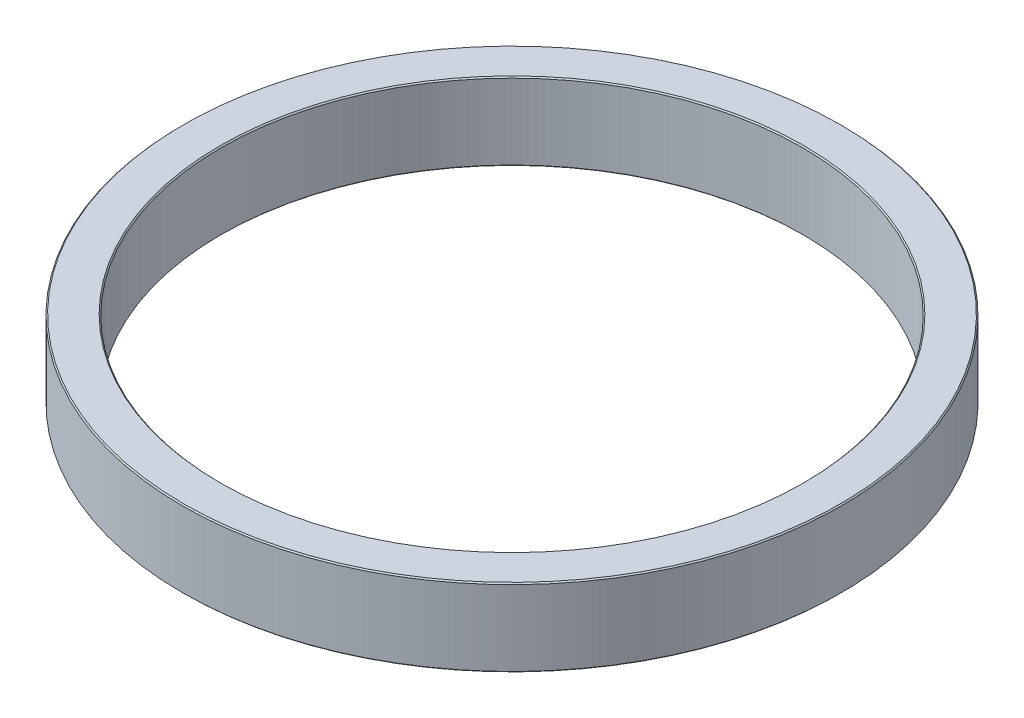
SolidWorks part; units mm, degrees
ref_plane "Front Plane" through (0, 0, 0) normal (0, 0, 1) x (1, 0, 0)
ref_plane "Top Plane" through (0, 0, 0) normal (0, 1, 0) x (1, 0, 0)
ref_plane "Right Plane" through (0, 0, 0) normal (1, 0, 0) x (0, 0, -1)
sketch "Sketch1" plane through (0, 0, 0) normal (0, 1, 0) x (1, 0, 0)
  circle A0 centre (0, 0) radius 37.5
  circle A1 centre (0, 0) radius 42.5
  dimension "D1" = 85
  dimension "D2" = 75
extrude "Boss-Extrude1" add sketch "Sketch1" along normal blind 10
chamfer "Chamfer1" distance 0.15 angle 45 4 edges at (0, 0, 42.5) (0, 10, 42.5) (0, 0, 37.5) (0, 10, 37.5)
